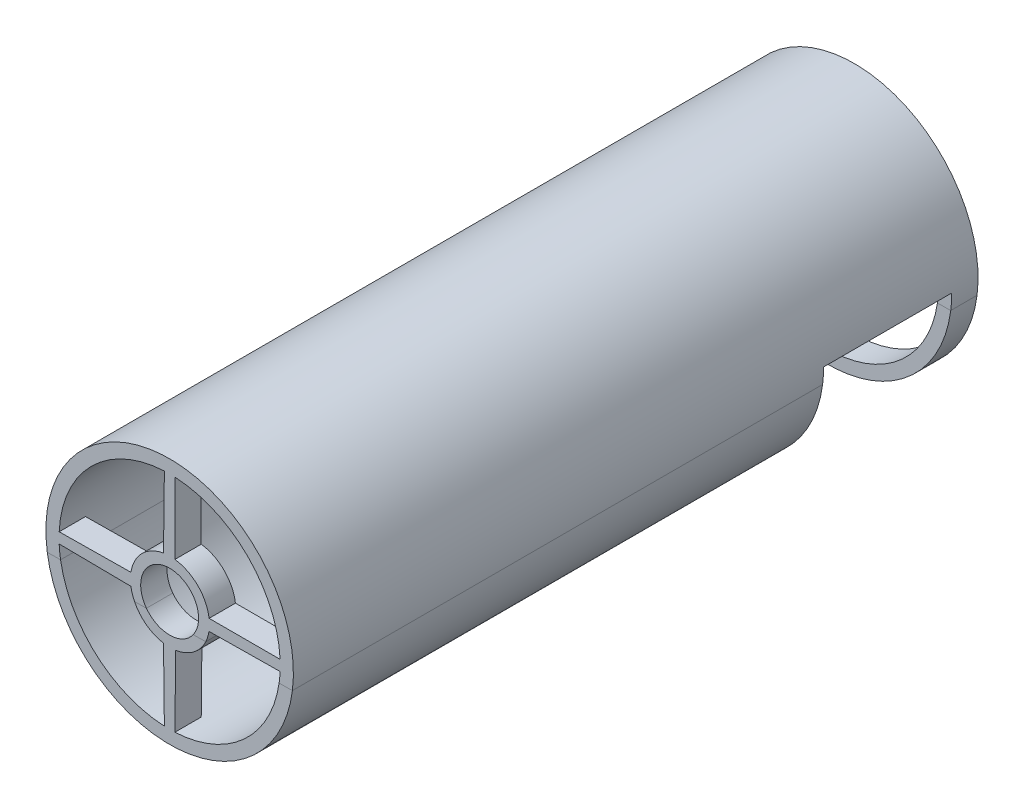
SolidWorks part; units mm, degrees
ref_plane "Front Plane" through (0, 0, 0) normal (0, 0, 1) x (1, 0, 0)
ref_plane "Top Plane" through (0, 0, 0) normal (0, 1, 0) x (1, 0, 0)
ref_plane "Right Plane" through (0, 0, 0) normal (1, 0, 0) x (0, 0, -1)
sketch "Sketch1" plane through (0, 0, 0) normal (0, 0, 1) x (1, 0, 0)
  circle A0 centre (0, 0) radius 26.67
  circle A1 centre (0, 0) radius 29.845
  dimension "D1" = 53.34
  dimension "D2" = 3.175
extrude "Boss-Extrude1" add sketch "Sketch1" along normal blind 165.1
sketch "Sketch2" plane through (0, 0, 0) normal (0, 1, 0) x (1, 0, 0)
  line L1 (-29.845, 0.8555) -> (29.845, 0.8555)
  line L2 (-29.845, 0.8555) -> (-29.845, -37.2445)
  line L3 (-29.845, -37.2445) -> (29.845, -37.2445)
  line L4 (29.845, 0.8555) -> (29.845, -37.2445)
  point P4 (0, 0.8555)
  dimension "D1" = 59.69
  dimension "D2" = 38.1
extrude "Cut-Extrude1" cut sketch "Sketch2" against normal through all
sketch "Sketch3" plane through (0, 0, 0) normal (0, 0, -1) x (-1, 0, 0)
  line L0 (-29.845, 0) -> (-13.97, 0)
  line L1 (13.97, 0) -> (29.845, 0)
  arc A0 (29.845, 0) -> (-29.845, 0) centre (0, 0) ccw construction
  arc A1 (29.845, 0) -> (-29.845, 0) centre (0, 0) ccw
  arc A2 (13.97, 0) -> (-13.97, 0) centre (0, 0) ccw
  point P3 (0, 0)
  point P6 (0, 0)
  point P7 (0.2728, 0)
  dimension "D1" = 13.97
extrude "Boss-Extrude2" add sketch "Sketch3" against normal blind 6.35
sketch "Sketch4" plane through (0, 0, 165.1) normal (0, 0, 1) x (1, 0, 0)
  line L0 (0, 0) -> (0, 26.67) construction
  line L1 (1.27, 26.6397) -> (1.27, 9.45)
  line L3 (9.5173, 1.27) -> (26.6397, 1.27)
  line L4 (29.818, 1.27) -> (30.6047, 1.27)
  line L5 (0, 0) -> (26.67, 0) construction
  line L7 (9.489, -1.4654) -> (26.6397, -1.27)
  line L8 (1.27, -26.6397) -> (1.4535, -9.4251)
  line L9 (-9.3342, 1.4654) -> (-26.6397, 1.27)
  line L10 (-1.27, 26.6397) -> (-1.4773, 9.3973)
  line L11 (-1.27, -26.6397) -> (-1.4773, -9.3973)
  line L12 (-9.3342, -1.4654) -> (-26.6397, -1.27)
  arc A0 (26.67, 0) -> (-26.67, 0) centre (0, 0) ccw construction
  circle A1 centre (0, 0) radius 29.845 construction
  circle A2 centre (0, 0) radius 29.845
  arc A3 (26.6397, 1.27) -> (1.27, 26.6397) centre (0, 0) ccw
  arc A4 (26.6397, -1.27) -> (1.27, -26.6397) centre (0, 0) cw
  arc A5 (-26.6397, 1.27) -> (-1.27, 26.6397) centre (0, 0) cw
  arc A6 (-26.6397, -1.27) -> (-1.27, -26.6397) centre (0, 0) ccw
  circle A7 centre (0, 0) radius 6.985
  arc A8 (-1.4773, 9.3973) -> (-9.3342, 1.4654) centre (0.0774, 0) ccw
  arc A9 (9.5173, 1.27) -> (1.27, 9.45) centre (0.0774, 0) ccw
  arc A10 (1.4535, -9.4251) -> (9.489, -1.4654) centre (0.0774, 0) ccw
  arc A11 (-9.3342, -1.4654) -> (-1.4773, -9.3973) centre (0.0774, 0) ccw
  circle M7 centre (0, 0) radius 29.845
  circle M8 centre (0, 0) radius 26.67
  dimension "D3" = 13.97
  dimension "D2" = 19.05
  dimension "D1" = 2.54
  dimension "D4" = 2.54
sketch "Sketch5" plane through (0, 0, 0) normal (0, 0, -1) x (-1, 0, 0)
  line L0 (-29.818, 1.27) -> (-30.6047, 1.27) construction
  line L1 (-29.818, 1.27) -> (-30.6047, 1.27)
  line L2 (26.6397, -1.27) -> (9.3342, -1.4654)
  line L3 (1.4773, -9.3973) -> (1.27, -26.6397)
  line L4 (26.6397, -1.27) -> (9.3342, -1.4654)
  line L5 (1.4773, -9.3973) -> (1.27, -26.6397)
  line L6 (9.3342, 1.4654) -> (26.6397, 1.27)
  line L7 (1.27, 26.6397) -> (1.4773, 9.3973)
  line L8 (9.3342, 1.4654) -> (26.6397, 1.27)
  line L9 (1.27, 26.6397) -> (1.4773, 9.3973)
  line L10 (-9.489, -1.4654) -> (-26.6397, -1.27)
  line L11 (-1.27, -26.6397) -> (-1.4535, -9.4251)
  line L12 (-9.489, -1.4654) -> (-26.6397, -1.27)
  line L13 (-1.27, -26.6397) -> (-1.4535, -9.4251)
  line L14 (-1.27, 9.45) -> (-1.27, 26.6397)
  line L15 (-26.6397, 1.27) -> (-9.5173, 1.27)
  line L16 (-1.27, 9.45) -> (-1.27, 26.6397)
  line L17 (-26.6397, 1.27) -> (-9.5173, 1.27)
  circle A1 centre (0, 0) radius 6.985
  circle A2 centre (0, 0) radius 6.985
  circle A3 centre (0, 0) radius 29.845
  circle A4 centre (0, 0) radius 29.845
  arc A6 (1.27, -26.6397) -> (26.6397, -1.27) centre (0, 0) ccw
  arc A7 (1.4773, -9.3973) -> (9.3342, -1.4654) centre (-0.0774, 0) ccw
  arc A8 (1.27, -26.6397) -> (26.6397, -1.27) centre (0, 0) ccw
  arc A9 (1.4773, -9.3973) -> (9.3342, -1.4654) centre (-0.0774, 0) ccw
  arc A10 (26.6397, 1.27) -> (1.27, 26.6397) centre (0, 0) ccw
  arc A11 (9.3342, 1.4654) -> (1.4773, 9.3973) centre (-0.0774, 0) ccw
  arc A12 (26.6397, 1.27) -> (1.27, 26.6397) centre (0, 0) ccw
  arc A13 (9.3342, 1.4654) -> (1.4773, 9.3973) centre (-0.0774, 0) ccw
  arc A14 (-26.6397, -1.27) -> (-1.27, -26.6397) centre (0, 0) ccw
  arc A15 (-9.489, -1.4654) -> (-1.4535, -9.4251) centre (-0.0774, 0) ccw
  arc A16 (-26.6397, -1.27) -> (-1.27, -26.6397) centre (0, 0) ccw
  arc A17 (-9.489, -1.4654) -> (-1.4535, -9.4251) centre (-0.0774, 0) ccw
  arc A18 (-1.27, 26.6397) -> (-26.6397, 1.27) centre (0, 0) ccw
  arc A19 (-1.27, 9.45) -> (-9.5173, 1.27) centre (-0.0774, 0) ccw
  arc A20 (-1.27, 26.6397) -> (-26.6397, 1.27) centre (0, 0) ccw
  arc A21 (-1.27, 9.45) -> (-9.5173, 1.27) centre (-0.0774, 0) ccw
  arc M19 (29.845, 0) -> (-29.845, 0) centre (0, 0) ccw
  line M20 (-29.845, 0) -> (-13.97, 0)
  arc M21 (-13.97, 0) -> (13.97, 0) centre (0, 0) cw
  line M22 (13.97, 0) -> (29.845, 0)
  dimension "D1" = 0
  dimension "D2" = 0
  dimension "D3" = 0
  dimension "D4" = 0
  dimension "D5" = 0
  dimension "D6" = 0
extrude "Boss-Extrude4" add sketch "Sketch5" against normal blind 6.35 contours A20 L16 L9 A12 L8 L17 M21 M22 M19 M20 | L16 A21 L17 A4 L8 A13 L9 A2 L5 A9 L4 A8 L12 A17 L13 A16 M21 M20 M22
extrude "Boss-Extrude5" add sketch "Sketch4" against normal blind 6.35 contours M7 M8 | L12 A11 L11 L8 A10 L7 L3 A9 L1 L10 A8 L9 A7 M8
ref_plane "Plane1" through (0.0469, -4.1131, 0) normal (-0.0114, 0.9999, 0) x (0.9999, 0.0114, 0)
sketch "Sketch6" plane through (0.0469, -4.1131, 0) normal (0.0114, -0.9999, 0) x (0.9999, 0.0114, 0)
  line L1 (-29.8803, 165.1047) -> (29.9378, 165.1047)
  line L2 (-29.8803, 165.1047) -> (-29.8803, -10.9054)
  line L3 (-29.8803, -10.9054) -> (29.9378, -10.9054)
  line L4 (29.9378, 165.1047) -> (29.9378, -10.9054)
split "Split4" trim tools "Plane1" bodies to split 106 resulting bodies 111 112 113
